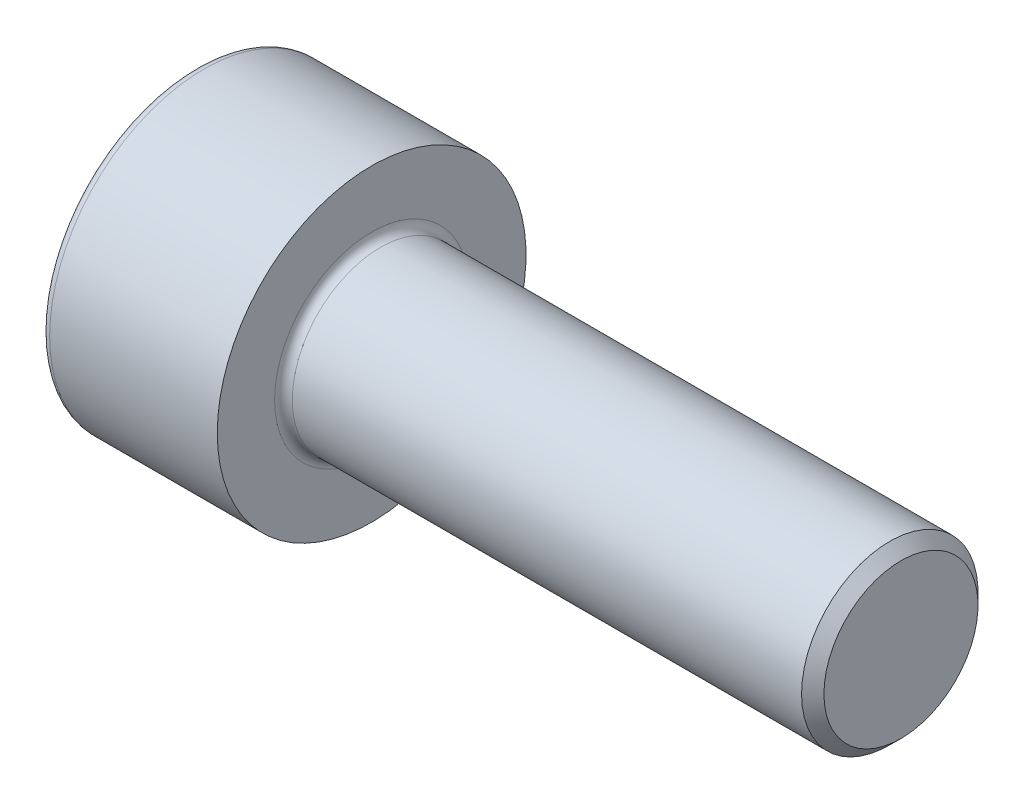
SolidWorks part; units mm, degrees
ref_plane "Front" through (0, 0, 0) normal (0, 0, 1) x (1, 0, 0)
ref_plane "Top" through (0, 0, 0) normal (0, 1, 0) x (1, 0, 0)
ref_plane "Right" through (0, 0, 0) normal (1, 0, 0) x (0, 0, -1)
sketch "Sketch1" plane through (0, 0, 0) normal (0, 0, 1) x (1, 0, 0)
  line L0 (11.7465, 2) -> (0.2, 2)
  line L1 (-4, 3.3) -> (-4, 0)
  line L2 (0, 3.5) -> (-3.8, 3.5)
  line L3 (0, 2.2) -> (0, 3.5)
  line L4 (12, 1.7465) -> (12, 0)
  line L5 (12, 1.7465) -> (11.7465, 2)
  line L6 (-4, 0) -> (0, 0) construction
  line L7 (-4, 0) -> (12, 0)
  arc A0 (-3.8, 3.5) -> (-4, 3.3) centre (-3.8, 3.3) ccw
  arc A1 (0, 2.2) -> (0.2, 2) centre (0.2, 2.2) ccw
  point P12 (0, 2.85)
  dimension "D5" = 0.2
  dimension "D1" = 4
  dimension "D2" = 7
  dimension "D3" = 135
  dimension "D4" = 0.3585
  dimension "D6" = 12
  dimension "D7" = 4
revolve "Revolve1" add sketch "Sketch1" angle 360 about L7
sketch "Sketch2" plane through (-4, 0, 0) normal (-1, 0, 0) x (0, 0, 1)
  line L7 (1.535, 0.8862) -> (0, 1.7725)
  line L8 (0, 1.7725) -> (-1.535, 0.8862)
  line L9 (-1.535, 0.8862) -> (-1.535, -0.8862)
  line L10 (-1.535, -0.8862) -> (0, -1.7725)
  line L11 (0, -1.7725) -> (1.535, -0.8862)
  line L12 (1.535, -0.8862) -> (1.535, 0.8862)
  circle A0 centre (0, 0) radius 1.535 construction
  dimension "D1" = 3.07
extrude "Cut-Extrude1" cut sketch "Sketch2" against normal blind 2
